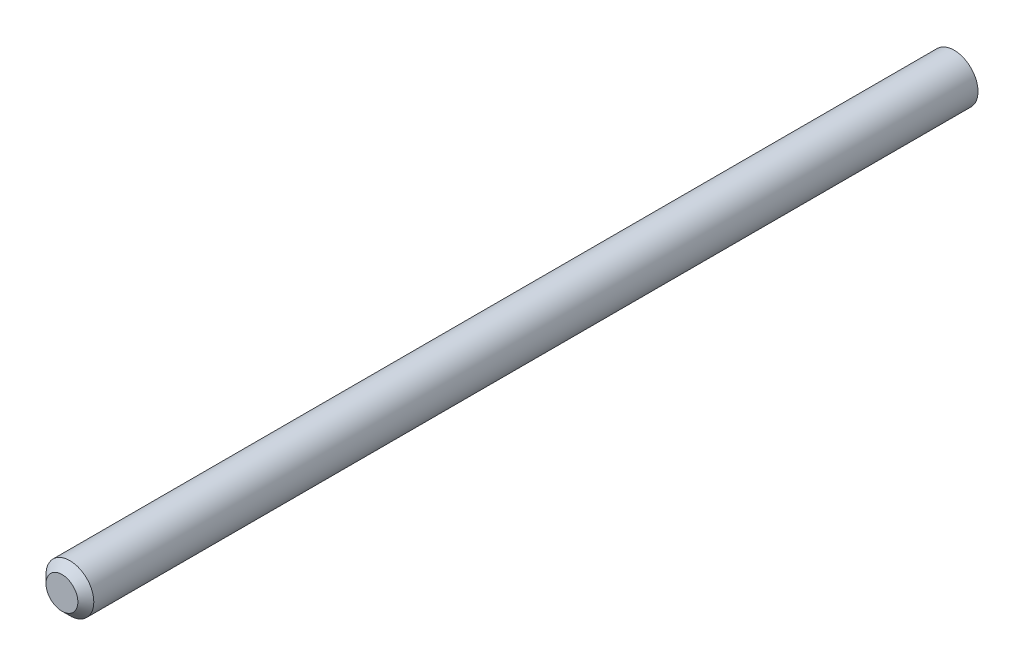
SolidWorks part; units mm, degrees
ref_plane "Front Plane" through (0, 0, 0) normal (0, 0, 1) x (1, 0, 0)
ref_plane "Top Plane" through (0, 0, 0) normal (0, 1, 0) x (1, 0, 0)
ref_plane "Right Plane" through (0, 0, 0) normal (1, 0, 0) x (0, 0, -1)
sketch "Sketch1" plane through (0, 0, 0) normal (0, 0, 1) x (1, 0, 0)
  circle A0 centre (0, 0) radius 9.525
  dimension "D1" = 19.05
extrude "Boss-Extrude1" add sketch "Sketch1" along normal blind 355.6
chamfer "Chamfer1" distance 3.175 angle 45 1 edges at (9.525, 0, 355.6)
